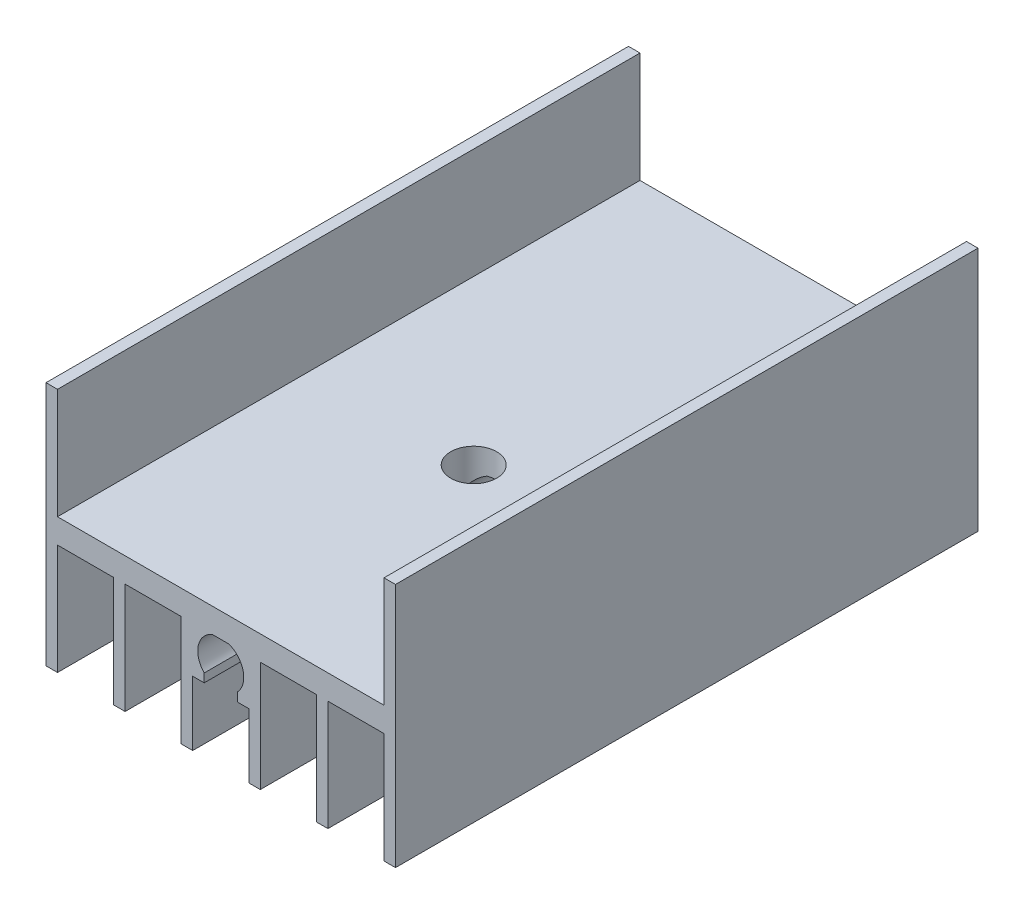
SolidWorks part; units mm, degrees
ref_plane "Front Plane" through (0, 0, 0) normal (0, 0, 1) x (1, 0, 0)
ref_plane "Top Plane" through (0, 0, 0) normal (0, 1, 0) x (1, 0, 0)
ref_plane "Right Plane" through (0, 0, 0) normal (1, 0, 0) x (0, 0, -1)
sketch "Sketch1" plane through (0, 0, 0) normal (0, 0, 1) x (1, 0, 0)
  line L0 (11.4, -8) -> (10.65, -8)
  line L1 (-11.4, -8) -> (11.4, -8)
  line L2 (-11.4, -8) -> (-11.4, 8)
  line L3 (-11.4, 8) -> (11.4, 8)
  line L4 (11.4, -8) -> (11.4, 8)
  line L5 (-11.4, -8) -> (11.4, 8) construction
  line L6 (-11.4, 8) -> (11.4, -8) construction
  line L7 (10.65, -8) -> (10.65, -0.8)
  line L8 (10.65, -0.8) -> (6.99, -0.8)
  line L9 (6.99, -0.8) -> (6.99, -8)
  line L10 (6.99, -8) -> (6.24, -8)
  line L11 (6.24, -8) -> (6.24, -0.8)
  line L12 (6.24, -0.8) -> (2.58, -0.8)
  line L13 (2.58, -0.8) -> (2.58, -8)
  line L14 (2.58, -8) -> (1.83, -8)
  line L15 (1.83, -8) -> (1.83, -0.8)
  line L16 (1.83, -0.8) -> (-1.83, -0.8)
  line L17 (-1.83, -0.8) -> (-1.83, -8)
  line L18 (-1.83, -8) -> (-2.58, -8)
  line L19 (-2.58, -8) -> (-2.58, -0.8)
  line L20 (-2.58, -0.8) -> (-6.24, -0.8)
  line L21 (-6.24, -0.8) -> (-6.24, -8)
  line L22 (-6.24, -8) -> (-6.99, -8)
  line L23 (-6.99, -8) -> (-6.99, -0.8)
  line L24 (-6.99, -0.8) -> (-10.65, -0.8)
  line L25 (-10.65, -0.8) -> (-10.65, -8)
  line L26 (-10.65, -8) -> (-11.4, -8)
  line L27 (11.4, 8) -> (10.65, 8)
  line L28 (10.65, 8) -> (10.65, 0.8)
  line L29 (10.65, 0.8) -> (-10.65, 0.8)
  line L30 (-10.65, 0.8) -> (-10.65, 8)
  line L31 (-10.65, 8) -> (-11.4, 8)
  line L32 (-1.83, -8) -> (-1.83, -3.8)
  line L33 (-1.83, -3.8) -> (-1.08, -3.8)
  line L34 (-1.08, -3.8) -> (-1.08, -3.241)
  line L35 (1.83, -8) -> (1.83, -3.8)
  line L36 (1.83, -3.8) -> (1.08, -3.8)
  line L37 (1.08, -3.8) -> (1.08, -3.241)
  arc A0 (1.08, -3.241) -> (-1.08, -3.241) centre (0, -2.2) ccw
  point P0 (0, 0)
  point P33 (0, -1.7024)
  point P38 (0, 0)
  point P39 (-1.2, -2.2395)
  point P40 (1.455, -3.8)
  point P41 (0, -2.1525)
  dimension "D14" = 3
  dimension "D15" = 1.5
  dimension "D1" = 22.8
  dimension "D2" = 16
  dimension "D3" = 0.75
  dimension "D4" = 0.75
  dimension "D5" = 0.75
  dimension "D6" = 0.75
  dimension "D7" = 0.75
  dimension "D8" = 0.75
  dimension "D9" = 3.66
  dimension "D10" = 3.66
  dimension "D11" = 3.66
  dimension "D12" = 3.66
  dimension "D13" = 1.6
  dimension "D16" = 11.4
  dimension "D17" = 0.75
  dimension "D18" = 0.75
  dimension "D19" = 3
  dimension "D20" = 3
  dimension "D21" = 7.2
extrude "Boss-Extrude1" add sketch "Sketch1" along normal blind 38 contours A0 L16 L15 L1 L13 L12 L11 L9 L8 L7 L0 L4 L3 L28 L29 L30 L2 L25 L24 L23 L21 L20 L19 L17 | A0 L16 L17 L33 L34 | L16 A0 | A0 L37 L36 L15 L16
sketch "Sketch2" plane through (0, 0.8, 0) normal (0, 1, 0) x (1, 0, 0)
  line L0 (11.4, -38) -> (11.4, 0) construction
  circle A0 centre (0, -21.5) radius 1.5
  dimension "D1" = 21.5
  dimension "D2" = 3
  dimension "D3" = 11.4
extrude "Cut-Extrude1" cut sketch "Sketch2" against normal blind 11
